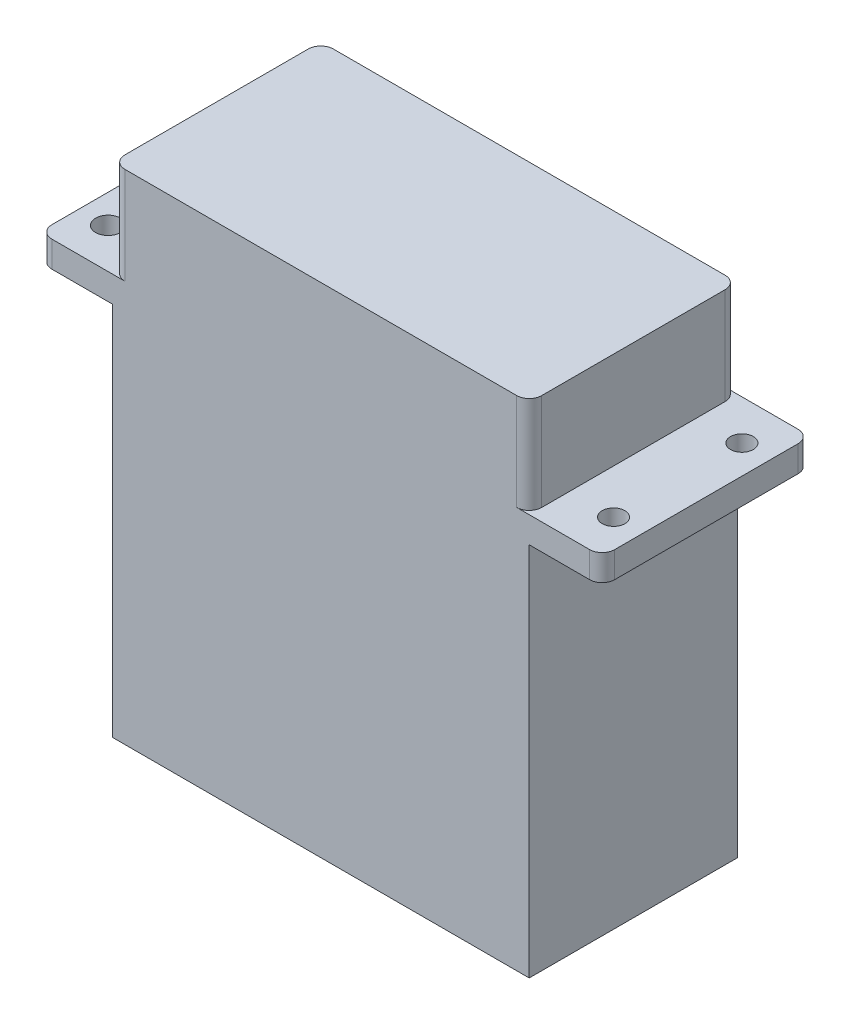
SolidWorks part; units mm, degrees
ref_plane "Front Plane" through (0, 0, 0) normal (0, 0, 1) x (1, 0, 0)
ref_plane "Top Plane" through (0, 0, 0) normal (0, 1, 0) x (1, 0, 0)
ref_plane "Right Plane" through (0, 0, 0) normal (1, 0, 0) x (0, 0, -1)
sketch "Sketch1" plane through (0, 0, 0) normal (0, 1, 0) x (1, 0, 0)
  line L0 (2.75, 16.159) -> (51.25, 16.159) construction
  line L1 (1.2, 0) -> (52.8, 0)
  line L2 (0, 1.2) -> (0, 18.8)
  line L3 (1.2, 20) -> (52.8, 20)
  line L4 (54, 1.2) -> (54, 18.8)
  line L5 (0, 10) -> (54, 10) construction
  arc A0 (52.8, 0) -> (54, 1.2) centre (52.8, 1.2) ccw
  arc A1 (0, 18.8) -> (1.2, 20) centre (1.2, 18.8) cw
  arc A2 (1.2, 0) -> (0, 1.2) centre (1.2, 1.2) cw
  arc A3 (52.8, 20) -> (54, 18.8) centre (52.8, 18.8) cw
  circle A4 centre (2.75, 16.159) radius 1.2
  circle A5 centre (51.25, 16.159) radius 1.0877
  circle A6 centre (51.25, 3.841) radius 1.0877
  circle A7 centre (2.75, 3.841) radius 1.2
  point P9 (0, 20)
  point P12 (0, 0)
  point P15 (54, 20)
  dimension "D3" = 1.2
  dimension "D5" = 2.75
  dimension "D1" = 20
  dimension "D2" = 54
  dimension "D4" = 48.5
extrude "Boss-Extrude1" add sketch "Sketch1" along normal blind 2.5
sketch "Sketch2" plane through (0, 2.5, 0) normal (0, 1, 0) x (1, 0, 0)
  line L0 (52.8, 20) -> (1.2, 20) construction
  line L1 (8.2, 20) -> (45.8, 20)
  line L2 (7, 18.8) -> (7, 1.2)
  line L3 (8.2, 0) -> (45.8, 0)
  line L4 (47, 18.8) -> (47, 1.2)
  line L5 (1.2, 0) -> (52.8, 0) construction
  line L6 (0, 18.8) -> (0, 1.2) construction
  line L7 (54, 1.2) -> (54, 18.8) construction
  arc A0 (8.2, 20) -> (7, 18.8) centre (8.2, 18.8) ccw
  arc A1 (7, 1.2) -> (8.2, 0) centre (8.2, 1.2) ccw
  arc A2 (45.8, 0) -> (47, 1.2) centre (45.8, 1.2) ccw
  arc A3 (45.8, 20) -> (47, 18.8) centre (45.8, 18.8) cw
  point P14 (7, 20)
  point P19 (47, 0)
  dimension "D3" = 1.2
  dimension "D1" = 7
  dimension "D2" = 7
extrude "Boss-Extrude2" add sketch "Sketch2" along normal blind 9.3
sketch "Sketch3" plane through (0, 0, 0) normal (0, -1, 0) x (1, 0, 0)
  line L0 (1.2, 0) -> (52.8, 0) construction
  line L1 (52.8, -20) -> (1.2, -20) construction
  line L2 (7, 0) -> (47, 0)
  line L3 (7, 0) -> (7, -20)
  line L4 (7, -20) -> (47, -20)
  line L5 (47, 0) -> (47, -20)
  line L6 (0, -18.8) -> (0, -1.2) construction
  line L7 (54, -1.2) -> (54, -18.8) construction
  dimension "D1" = 7
  dimension "D2" = 7
extrude "Boss-Extrude3" add sketch "Sketch3" along normal blind 36
